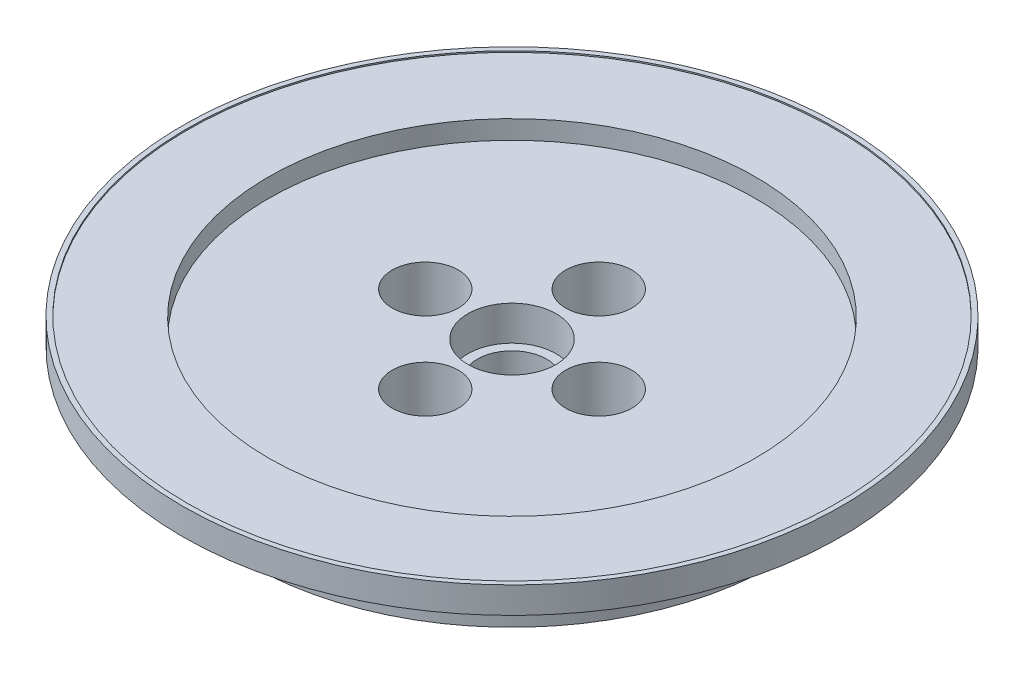
SolidWorks part; units mm, degrees
ref_plane "Front Plane" through (0, 0, 0) normal (0, 0, 1) x (1, 0, 0)
ref_plane "Top Plane" through (0, 0, 0) normal (0, 1, 0) x (1, 0, 0)
ref_plane "Right Plane" through (0, 0, 0) normal (1, 0, 0) x (0, 0, -1)
ref_plane "Plane1" through (0, 0, 0) normal (0, 0, -1) x (-1, 0, 0)
sketch "Sketch1" plane through (0, 0, 0) normal (0, 0, -1) x (-1, 0, 0)
  line L0 (-38.1, -11.938) -> (0, -11.938)
  line L1 (0, -11.938) -> (0, 0)
  line L2 (0, 0) -> (-47.498, 0)
  line L3 (-47.498, 0) -> (-47.498, -3.81)
  line L4 (-47.498, -3.81) -> (-38.1, -7.2306)
  line L5 (-38.1, -7.2306) -> (-38.1, -11.938)
  line L6 (0, -11.938) -> (0, 0) construction
revolve "Revolve1" add sketch "Sketch1" angle 360 about L6
sketch "Sketch2" plane through (0, 0, 0) normal (0, 0, -1) x (-1, 0, 0)
  line L0 (-5, -11.938) -> (0, -11.938)
  line L1 (0, -11.938) -> (0, 0)
  line L2 (0, 0) -> (-46.798, 0)
  line L3 (-46.798, 0) -> (-46.798, -0.2)
  line L4 (-46.798, -0.2) -> (-35.1, -0.2)
  line L5 (-35.1, -0.2) -> (-35.1, -2.9)
  line L6 (-35.1, -2.9) -> (-6.35, -2.9)
  line L7 (-6.35, -2.9) -> (-6.35, -7.898)
  line L8 (-6.35, -7.898) -> (-5, -7.898)
  line L9 (-5, -7.898) -> (-5, -11.938)
  line L10 (0, -11.938) -> (0, 0) construction
revolve "Cut-Revolve1" cut sketch "Sketch2" angle 360 about L10
hole_wizard "M8 Clearance Hole1" positions "Sketch4" profile "Sketch3" hole size "M8" standard "ANSI Metric"
sketch "Sketch4" plane through (0, -11.938, 0) normal (0, -1, 0) x (-1, 0, 0)
  point P0 (0, -12.5)
  point P1 (-12.5, 0)
  point P2 (0, 12.5)
  point P3 (12.5, 0)
sketch "Sketch3" plane through (0, -11.938, 12.5) normal (1, 0, 0) x (0, 0, -1)
  line L0 (0, 0) -> (0, 11.938)
  line L1 (0, 11.938) -> (4.7625, 11.938)
  line L2 (4.7625, 11.938) -> (4.7625, 0)
  line L5 (4.7625, 0) -> (0, 0)
  line L11 (0, -6.35) -> (0, 107.95) construction
  dimension "Thru Hole Dia." = 9.525
  dimension "Thru Hole Depth" = 11.938
